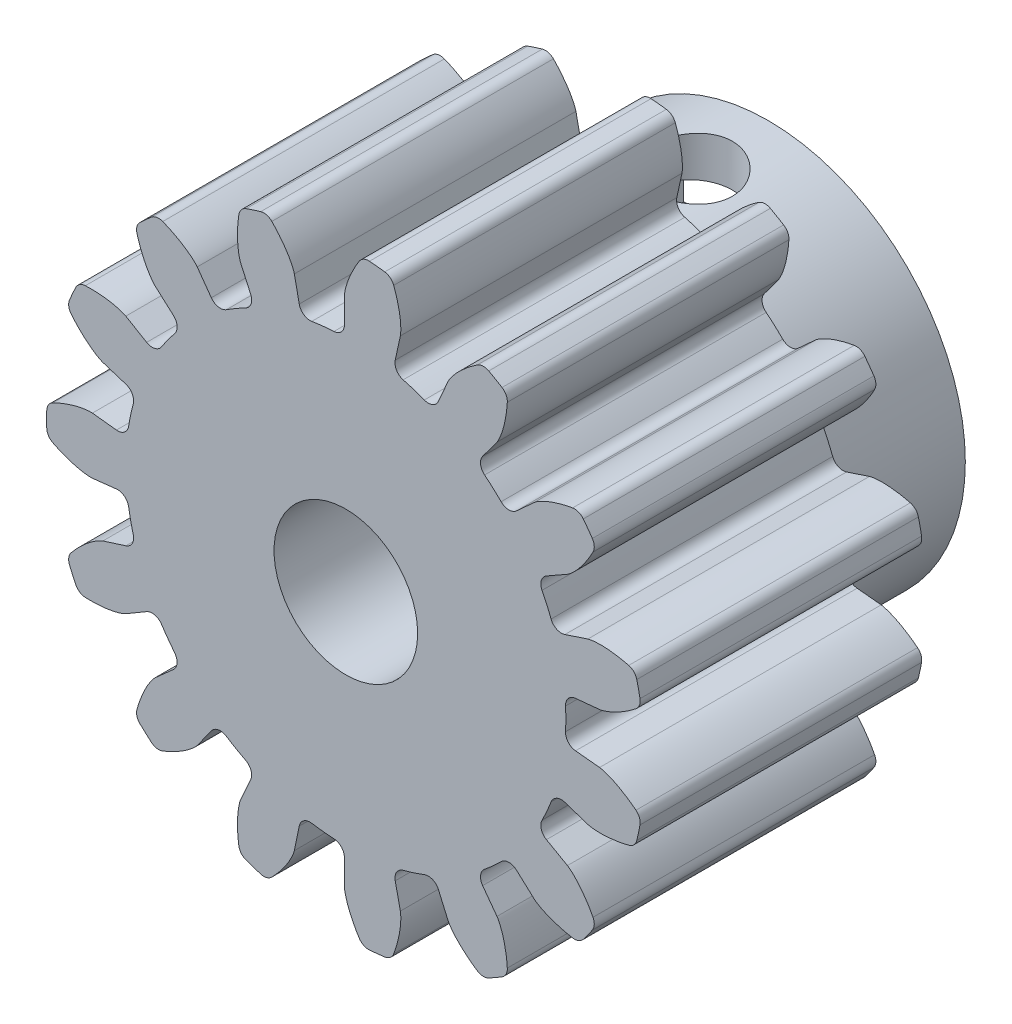
SolidWorks part; units mm, degrees
material "Brass"
ref_plane "Front Plane" through (0, 0, 0) normal (0, 0, 1) x (1, 0, 0)
ref_plane "Top Plane" through (0, 0, 0) normal (0, 1, 0) x (1, 0, 0)
ref_plane "Right Plane" through (0, 0, 0) normal (1, 0, 0) x (0, 0, -1)
sketch "Sketch1" plane through (0, 0, 0) normal (0, 0, 1) x (1, 0, 0)
  circle A0 centre (0, 0) radius 10.625
  dimension "D1" = 21.25
extrude "Boss-Extrude1" add sketch "Sketch1" along normal blind 10
sketch "Sketch2" plane through (0, 0, 10) normal (0, 0, 1) x (1, 0, 0)
  line L0 (9.0116, 0.8912) -> (0, 0) construction
  line L1 (0, 0) -> (9.0116, -0.8912) construction
  line L2 (7.7746, 0.7688) -> (9.0116, 0.8912)
  line L3 (7.7746, -0.7688) -> (9.0116, -0.8912)
  circle A0 centre (0, 0) radius 10.625 construction
  circle A1 centre (0, 0) radius 9.0556 construction
  circle A2 centre (0, 0) radius 9.375 construction
  circle A3 centre (0, 0) radius 7.8125 construction
  arc A4 (10.4861, 1.7121) -> (10.4861, -1.7121) centre (3.6281, 0) cw
  arc A5 (7.7746, -0.7688) -> (7.7746, 0.7688) centre (0, 0) ccw
  spline S0 degree 4 poles (9.0116, 0.8912) (9.0141, 0.8914) (9.0211, 0.8923) (9.0343, 0.8944) (9.0558, 0.8984) (9.0831, 0.9042) (9.1182, 0.9128) (9.1594, 0.924) (9.2044, 0.9377) (9.253, 0.9539) (9.3013, 0.9713) (9.3493, 0.9897) (9.3968, 1.0091) (9.454, 1.0338) (9.5223, 1.065) (9.6014, 1.1039) (9.6903, 1.1508) (9.78, 1.2016) (9.8675, 1.2541) (9.9551, 1.3098) (10.0391, 1.3657) (10.1254, 1.4266) (10.2045, 1.4842) (10.292, 1.5519) (10.3622, 1.6074) (10.4536, 1.6839) (10.5072, 1.7301) (10.5694, 1.7852) (10.5968, 1.8103) (10.6137, 1.8257) knots 0 0 0 0 0 0.005377 0.015084 0.028532 0.04661 0.064855 0.092111 0.119476 0.146842 0.174209 0.201575 0.228941 0.256307 0.307035 0.361767 0.4165 0.471232 0.525964 0.580697 0.635429 0.690161 0.744894 0.799626 0.854358 0.909091 0.954545 1 1 1 1 1 construction
  spline S1 degree 4 poles (9.0116, 0.8912) (9.0141, 0.8914) (9.0211, 0.8923) (9.0343, 0.8944) (9.0558, 0.8984) (9.0831, 0.9042) (9.1182, 0.9128) (9.1594, 0.924) (9.2044, 0.9377) (9.253, 0.9539) (9.3013, 0.9713) (9.3493, 0.9897) (9.3968, 1.0091) (9.454, 1.0338) (9.5223, 1.065) (9.6014, 1.1039) (9.6903, 1.1508) (9.78, 1.2016) (9.8675, 1.2541) (9.9551, 1.3098) (10.0391, 1.3657) (10.1254, 1.4266) (10.2045, 1.4842) (10.292, 1.5519) (10.3622, 1.6074) (10.4338, 1.6673) (10.4685, 1.6969) (10.4861, 1.7121) knots 0 0 0 0 0 0.005377 0.015084 0.028532 0.04661 0.064855 0.092111 0.119476 0.146842 0.174209 0.201575 0.228941 0.256307 0.307035 0.361767 0.4165 0.471232 0.525964 0.580697 0.635429 0.690161 0.744894 0.799626 0.854358 0.909091 0.909091 0.909091 0.909091 0.909091
  spline S2 degree 4 poles (9.0116, -0.8912) (9.0141, -0.8914) (9.0211, -0.8923) (9.0343, -0.8944) (9.0558, -0.8984) (9.0831, -0.9042) (9.1182, -0.9128) (9.1594, -0.924) (9.2044, -0.9377) (9.253, -0.9539) (9.3013, -0.9713) (9.3493, -0.9897) (9.3968, -1.0091) (9.454, -1.0338) (9.5223, -1.065) (9.6014, -1.1039) (9.6903, -1.1508) (9.78, -1.2016) (9.8675, -1.2541) (9.9551, -1.3098) (10.0391, -1.3657) (10.1254, -1.4266) (10.2045, -1.4842) (10.292, -1.5519) (10.3622, -1.6074) (10.4536, -1.6839) (10.5072, -1.7301) (10.5694, -1.7852) (10.5968, -1.8103) (10.6137, -1.8257) knots 0 0 0 0 0 0.005377 0.015084 0.028532 0.04661 0.064855 0.092111 0.119476 0.146842 0.174209 0.201575 0.228941 0.256307 0.307035 0.361767 0.4165 0.471232 0.525964 0.580697 0.635429 0.690161 0.744894 0.799626 0.854358 0.909091 0.954545 1 1 1 1 1 construction
  spline S3 degree 4 poles (9.0116, -0.8912) (9.0141, -0.8914) (9.0211, -0.8923) (9.0343, -0.8944) (9.0558, -0.8984) (9.0831, -0.9042) (9.1182, -0.9128) (9.1594, -0.924) (9.2044, -0.9377) (9.253, -0.9539) (9.3013, -0.9713) (9.3493, -0.9897) (9.3968, -1.0091) (9.454, -1.0338) (9.5223, -1.065) (9.6014, -1.1039) (9.6903, -1.1508) (9.78, -1.2016) (9.8675, -1.2541) (9.9551, -1.3098) (10.0391, -1.3657) (10.1254, -1.4266) (10.2045, -1.4842) (10.292, -1.5519) (10.3622, -1.6074) (10.4338, -1.6673) (10.4685, -1.6969) (10.4861, -1.7121) knots 0 0 0 0 0 0.005377 0.015084 0.028532 0.04661 0.064855 0.092111 0.119476 0.146842 0.174209 0.201575 0.228941 0.256307 0.307035 0.361767 0.4165 0.471232 0.525964 0.580697 0.635429 0.690161 0.744894 0.799626 0.854358 0.909091 0.909091 0.909091 0.909091 0.909091
  circle M4 centre (0, 0) radius 10.625
  dimension "D1" = 21.25
  dimension "D2" = 15.625
  dimension "D3" = 18.75
  dimension "D4" = 18.1111
extrude "Cut-Extrude1" cut sketch "Sketch2" against normal through all contours L3 S3 S1 L2 A5 M4
sketch "Mate" plane through (0, 0, 0) normal (0, 0, 1) x (1, 0, 0)
  circle A0 centre (0, 0) radius 9.375
  circle A1 centre (0, 0) radius 9.375 construction
fillet "Fillet1" radius 0.3934 4 edges at (7.7746, -0.7688, 5) (7.7746, 0.7688, 5) (10.4861, -1.7121, 5) (10.4861, 1.7121, 5)
pattern_circular "CirPattern1" count 15 over 360 about axis through (0, 0, 0) along (0, 0, 1) of "Cut-Extrude1", "Fillet1"
sketch "Sketch4" plane through (0, 0, 0) normal (0, 0, 1) x (1, 0, 0)
  circle A0 centre (0, 0) radius 7
  dimension "D1" = 14
extrude "Boss-Extrude2" add sketch "Sketch4" against normal blind 5
sketch "Sketch3" plane through (0, 0, 0) normal (0, 0, 1) x (1, 0, 0)
  circle A0 centre (0, 0) radius 2.55
  dimension "D1" = 5.1
extrude "Cut-Extrude2" cut sketch "Sketch3" along normal through all both and the other way through all
sketch "Sketch5" plane through (0, 0, 0) normal (0, 1, 0) x (1, 0, 0)
  circle A0 centre (0, 2.2) radius 1.525
  dimension "D1" = 3.05
  dimension "D2" = 2.2
extrude "Cut-Extrude3" cut sketch "Sketch5" along normal through all
sketch "Sketch6" plane through (0, 0, 0) normal (0, 1, 0) x (1, 0, 0)
  line L0 (3, 2.2) -> (3, 6.8389)
  line L1 (3, 2.2) -> (1.5, 4.7981)
  line L2 (1.5, 4.7981) -> (-1.5, 4.7981)
  line L3 (-1.5, 4.7981) -> (-3, 2.2)
  line L4 (-3, 2.2) -> (-1.5, -0.3981)
  line L5 (-1.5, -0.3981) -> (1.5, -0.3981)
  line L6 (1.5, -0.3981) -> (3, 2.2)
  line L7 (3, 6.8389) -> (-3, 6.8389)
  line L8 (-3, 6.8389) -> (-3, 2.2)
  circle A0 centre (0, 2.2) radius 2.5981 construction
  dimension "D1" = 6
extrude "Cut-Extrude4" cut sketch "Sketch6" against normal blind 2.5 from offset 5.5 contours L7 L8 L3 L2 L1 L0 | L5 L6 L1 L2 L3 L4
equation "\"DiametralPitch\"= 0.8"
equation "\"NumTeeth\"= 15"
equation "\"Addendum\"= 1 / \"DiametralPitch\""
equation "\"Dedendum\"= 1.25 / \"DiametralPitch\""
equation "\"WorkingDepth\"= 2 / \"DiametralPitch\""
equation "\"WholeDepth\"= 2.25 / \"DiametralPitch\""
equation "\"Clearance\"= 0.25 / \"DiametralPitch\""
equation "\"ToothThickness\"= 1.5708 / \"DiametralPitch\""
equation "\"CircularPitch\"= pi / \"DiametralPitch\""
equation "\"PitchCircle\"= \"NumTeeth\" / \"DiametralPitch\""
equation "\"OutsideDiameter\"= ( \"NumTeeth\" + 2 ) / \"DiametralPitch\""
equation "\"AddendumCircle\"= \"PitchCircle\" + ( 2 * \"Addendum\" )"
equation "\"DedendumCircle\"= \"PitchCircle\" - ( 2 * \"Dedendum\" )"
equation "\"PitchAngle\"= 360deg / \"NumTeeth\""
equation "\"PressureAngle\"= 15deg"
equation "\"Width\"= 10mm"
equation "\"Fillet\"= \"Clearance\" * cos ( \"PressureAngle\" ) * tan ( ( 90 + \"PressureAngle\" ) / 2 )"
equation "\"BaseCircle\"= \"PitchCircle\" * cos ( \"PressureAngle\" )"
equation "\"Alpha\"= sqr ( \"PitchCircle\" ^ 2 - \"BaseCircle\" ^ 2 ) / \"BaseCircle\" * 180 / PI - \"PressureAngle\""
equation "\"Beta\"= ( \"PitchAngle\" / 4 - \"Alpha\" )"
equation "\"Phi\"= sqr ( ( \"AddendumCircle\" / 2 ) ^ 2 - ( \"BaseCircle\" / 2 ) ^ 2 ) / ( \"BaseCircle\" / 2 )"
equation "\"D1@Sketch1\"=\"OutsideDiameter\""
equation "\"D1@Boss-Extrude1\"=\"Width\""
equation "\"D1@Sketch2\"=\"OutsideDiameter\""
equation "\"D2@Sketch2\"=\"DedendumCircle\""
equation "\"D3@Sketch2\"=\"PitchCircle\""
equation "\"D4@Sketch2\"=\"BaseCircle\""
equation "\"D1@Fillet1\"=\"Fillet\""
equation "\"D1@CirPattern1\"=\"NumTeeth\""
